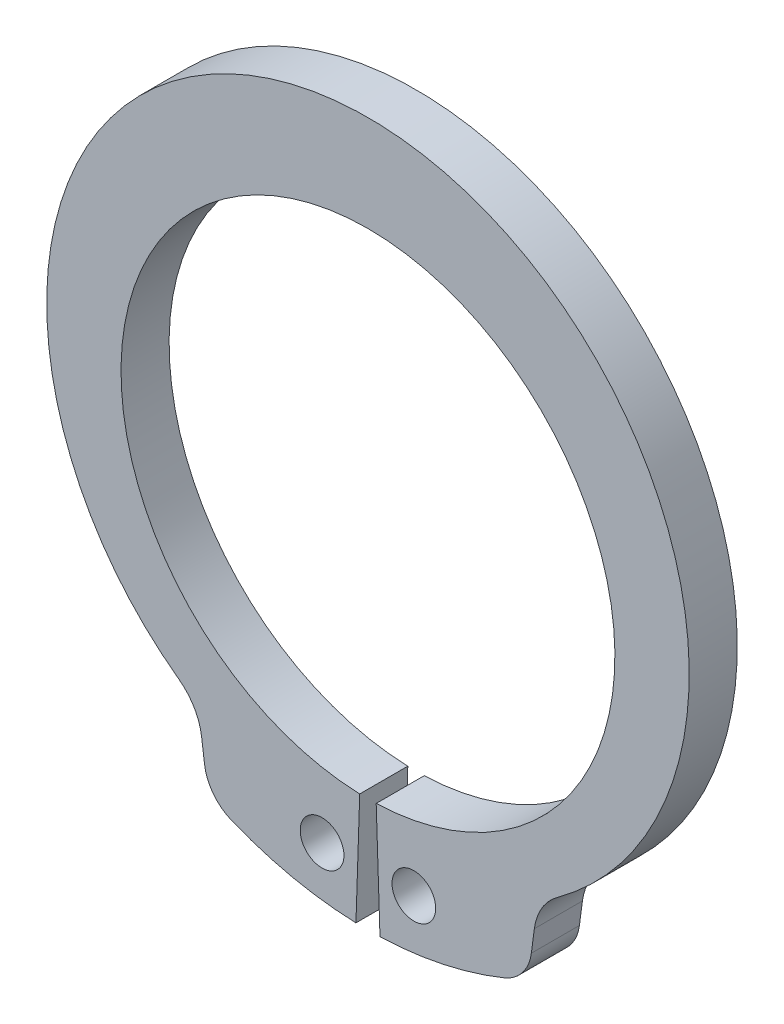
SolidWorks part; units mm, degrees
material "AISI 1020"
ref_plane "Plane1" through (0, 0, 0) normal (0, 0, 1) x (1, 0, 0)
ref_plane "Plane2" through (0, 0, 0) normal (0, 1, 0) x (1, 0, 0)
ref_plane "Plane3" through (0, 0, 0) normal (1, 0, 0) x (0, 0, -1)
other "Configuration Table"
sketch "Clipboard" plane through (0, 0, 0) normal (0, 0, 1) x (1, 0, 0)
  line L0 (0, 0) -> (2.2, 0)
  line L1 (0, 0) -> (0, 1.3)
  line L2 (0, 0) -> (0, -2.6)
  circle A0 centre (0, 0) radius 0.5
  circle A1 centre (0, 0) radius 6
  dimension "HoleDia" = 1
  dimension "ShaftDia" = 12
  dimension "LargeSection" = 2.2
  dimension "SmallSection" = 1.3
  dimension "LugSection" = 2.6
sketch "BodySke" plane through (0, 0, 0) normal (0, 0, 1) x (1, 0, 0)
  line L0 (-1.5431, 0) -> (1.5431, 0) construction
  line L1 (0, 0) -> (0, 7.85) construction
  line L2 (0.1883, -5.6469) -> (0.275, -8.2454)
  line L3 (-0.1883, -5.6469) -> (-0.275, -8.2454)
  line L4 (0, 0) -> (5.0945, -6.4891) construction
  line L5 (0, 0) -> (-5.0945, -6.4891) construction
  line L7 (3.8066, -6.3195) -> (3.7381, -6.8401)
  line L8 (-3.8066, -6.3195) -> (-3.7381, -6.8401)
  circle A0 centre (0, 0) radius 5.65 construction
  arc A1 (0.1883, -5.6469) -> (-0.1883, -5.6469) centre (0, 0) ccw
  arc A2 (4.2917, -5.4666) -> (-4.2917, -5.4666) centre (0, 0.5001) ccw construction
  arc A3 (0.275, -8.2454) -> (3.1255, -7.635) centre (0, 0) ccw
  arc A4 (4.3293, -5.4393) -> (3.8066, -6.3195) centre (5.0945, -6.4891) ccw
  arc A5 (-3.8066, -6.3195) -> (-4.3293, -5.4393) centre (-5.0945, -6.4891) ccw
  arc A6 (-3.1255, -7.635) -> (-0.275, -8.2454) centre (0, 0) ccw
  arc A7 (4.3293, -5.4393) -> (-4.3293, -5.4393) centre (0, 0.5001) ccw
  arc A8 (-3.8492, -5.9958) -> (3.8492, -5.9958) centre (0, 0) ccw construction
  circle A9 centre (1.05, -7.0472) radius 0.5
  circle A10 centre (-1.05, -7.0472) radius 0.5
  arc A11 (3.7381, -6.8401) -> (3.1255, -7.635) centre (2.7466, -6.7096) cw
  arc A12 (-3.7381, -6.8401) -> (-3.1255, -7.635) centre (-2.7466, -6.7096) ccw
  point P28 (3.6655, -7.391)
  point P31 (-3.6655, -7.391)
  dimension "GrooveDia" = 11.3
  dimension "LugRad" = 8.25
  dimension "HoleOffsetRad" = 7.125
  dimension "HoleDia" = 1
  dimension "D3" = 1
  dimension "LargeRad" = 7.85
  dimension "SmallRad" = 6.95
  dimension "SmallAngle" = 76.27
  dimension "D2" = 15
  dimension "HoleSpacing" = 2.1
  dimension "Gap" = 0.55
extrude "Body" add sketch "BodySke" against normal blind 1.1
sketch "NotSke" plane through (0, 0, 0) normal (0, 0, 1) x (1, 0, 0)
  line L0 (1.05, -6.5472) -> (1.05, -7.5472)
  line L1 (1.05, -7.5472) -> (-1.05, -7.5472)
  line L2 (-1.05, -7.5472) -> (-1.05, -6.5472)
  line L3 (-1.05, -6.5472) -> (1.05, -6.5472)
  circle A0 centre (1.05, -7.0472) radius 0.5 construction
  circle A1 centre (-1.05, -7.0472) radius 0.5 construction
extrude "Notch" [suppressed] cut sketch "NotSke" against normal through all
equation "' \"ShaftDia@Clipboard\" = 10"
equation "' \"Thickness@Body\" = 0.9"
equation "' \"GrooveDia@BodySke\" = 9.4"
equation "' \"LugSection@Clipboard\" = 2.6"
equation "' \"LargeSection@Clipboard\" = 1.7"
equation "' \"SmallSection@Clipboard\" = 1.0"
equation "' \"HoleDia@Clipboard\" = 1.0"
equation "' \"ShaftDia@Clipboard\" = 30"
equation "' \"Thickness@Body\" = 2.4"
equation "' \"GrooveDia@BodySke\" = 28.2"
equation "' \"LugSection@Clipboard\" = 5.6"
equation "' \"LargeSection@Clipboard\" = 4.5"
equation "' \"SmallSection@Clipboard\" = 2.5"
equation "' \"HoleDia@Clipboard\" = 2.3"
equation "\"Gap@BodySke\" =  \"Thickness@Body\" / 2"
equation "\"LargeRad@BodySke\" =  \"GrooveDia@BodySke\" / 2 +  \"LargeSection@Clipboard\""
equation "\"SmallRad@BodySke\" =  \"GrooveDia@BodySke\" / 2 +  \"SmallSection@Clipboard\""
equation "\"LugRad@BodySke\" = \"GrooveDia@BodySke\" / 2 + \"LugSection@Clipboard\""
equation "\"HoleOffsetRad@BodySke\" = (  \"ShaftDia@Clipboard\" / 2 + \"LugRad@BodySke\" ) / 2"
equation "\"HoleSpacing@BodySke\" = \"Gap@BodySke\"  * 2 +  \"HoleDia@Clipboard\""
equation "\"HoleDia@BodySke\" =  \"HoleDia@Clipboard\""
equation "\"SmallAngle@BodySke\" = atn(\"HoleSpacing@BodySke\" / 2 / sqr(\"HoleOffsetRad@BodySke\"  * \"HoleOffsetRad@BodySke\" - (\"HoleSpacing@BodySke\" / 2) * (\"HoleSpacing@BodySke\" / 2) ))  * 9 * ( 180 / 3.141593)"
